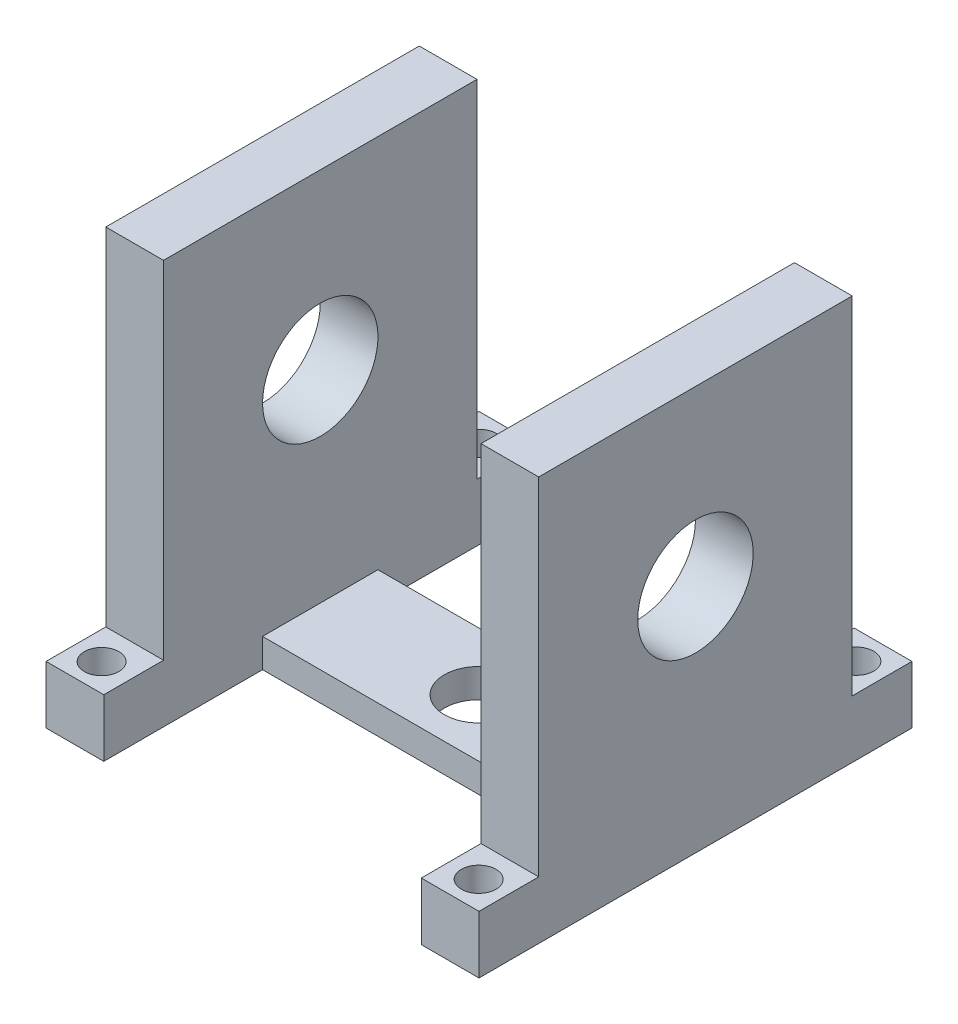
SolidWorks part; units mm, degrees
ref_plane "Front Plane" through (0, 0, 0) normal (0, 0, 1) x (1, 0, 0)
ref_plane "Top Plane" through (0, 0, 0) normal (0, 1, 0) x (1, 0, 0)
ref_plane "Right Plane" through (0, 0, 0) normal (1, 0, 0) x (0, 0, -1)
sketch "Sketch1" plane through (0, 0, 0) normal (0, 1, 0) x (1, 0, 0)
  line L0 (0, 0) -> (0, 37.5) construction
  line L1 (37.5, 37.5) -> (-37.5, 37.5)
  line L2 (37.5, 37.5) -> (37.5, -37.5)
  line L3 (37.5, -37.5) -> (-37.5, -37.5)
  line L4 (-37.5, 37.5) -> (-37.5, -37.5)
  line L5 (0, 0) -> (-37.5, 0) construction
  circle A0 centre (-32.66, 32.72) radius 3
  circle A1 centre (32.66, 32.72) radius 3
  circle A2 centre (32.66, -32.72) radius 3
  circle A3 centre (-32.66, -32.72) radius 3
  circle A4 centre (0, 0) radius 6
  point P0 (0, 0)
  point P11 (0, -37.5)
  dimension "D3" = 6
  dimension "D5" = 12
  dimension "D1" = 4.84
  dimension "D2" = 75
  dimension "D4" = 75
  dimension "D6" = 65.44
extrude "Boss-Extrude1" add sketch "Sketch1" along normal blind 10
sketch "Sketch2" plane through (0, 10, 0) normal (0, 1, 0) x (1, 0, 0)
  line L0 (-37.5, 37.5) -> (-37.5, -37.5) construction
  line L1 (-37.5, 27.1541) -> (-27.5, 27.1541)
  line L2 (-37.5, 27.1541) -> (-37.5, -27.1541)
  line L3 (0, 0) -> (0, 27.1541) construction
  line L4 (-27.5, 27.1541) -> (-27.5, -27.1541)
  line L5 (0, 0) -> (-23.3341, 0) construction
  line L6 (-37.5, -27.1541) -> (-27.5, -27.1541)
  line L7 (37.5, -27.1541) -> (27.5, -27.1541)
  line L8 (27.5, 27.1541) -> (27.5, -27.1541)
  line L9 (37.5, 27.1541) -> (37.5, -27.1541)
  line L10 (37.5, 27.1541) -> (27.5, 27.1541)
  point P12 (-27.5, 0)
  point P13 (-37.5, 0)
  point P17 (37.5, 0)
  point P18 (27.5, 0)
  dimension "D1" = 10
extrude "Boss-Extrude2" add sketch "Sketch2" along normal blind 60
sketch "Sketch3" plane through (-37.5, 0, 0) normal (-1, 0, 0) x (0, 0, 1)
  line L0 (0, 70) -> (0, 0) construction
  line L1 (-27.1541, 70) -> (27.1541, 70) construction
  line L2 (-27.1541, 40) -> (27.1541, 40) construction
  line L3 (-27.1541, 70) -> (-27.1541, 10) construction
  line L4 (27.1541, 70) -> (27.1541, 10) construction
  circle A0 centre (0, 40) radius 10
  dimension "D1" = 20
extrude "Cut-Extrude1" cut sketch "Sketch3" against normal through all both and the other way through all
sketch "Sketch4" plane through (0, 10, 0) normal (0, 1, 0) x (1, 0, 0)
  line L0 (0, 37.5) -> (0, -19.9966) construction
  line L1 (37.5, 37.5) -> (-37.5, 37.5) construction
  line L2 (-27.5, -27.1541) -> (-27.5, 27.1541) construction
  line L3 (27.5, -10) -> (-27.5, -10)
  line L4 (27.5, -10) -> (27.5, 10)
  line L5 (27.5, 10) -> (-27.5, 10)
  line L6 (-27.5, -10) -> (-27.5, 10)
  line L7 (27.5, -10) -> (-27.5, 10) construction
  line L8 (27.5, 10) -> (-27.5, -10) construction
  line L9 (-37.5, -37.5) -> (37.5, -37.5) construction
  line L10 (-27.5, 10) -> (27.5, 10)
  line L11 (-27.5, 10) -> (-27.5, 37.5)
  line L12 (-27.5, 37.5) -> (27.5, 37.5)
  line L13 (27.5, 10) -> (27.5, 37.5)
  line L14 (-27.5, -10) -> (27.5, -10)
  line L15 (-27.5, -10) -> (-27.5, -37.5)
  line L16 (-27.5, -37.5) -> (27.5, -37.5)
  line L17 (27.5, -10) -> (27.5, -37.5)
  point P5 (0, 0)
  point P13 (27.5, 0)
  line M13 (37.5, 37.5) -> (-37.5, 37.5)
  line M16 (-27.5, 27.1541) -> (-27.5, -27.1541)
  line M19 (-37.5, -37.5) -> (37.5, -37.5)
  line M22 (27.5, -27.1541) -> (27.5, 27.1541)
  dimension "D1" = 20
extrude "Cut-Extrude2" cut sketch "Sketch4" against normal through all both and the other way through all contours L13 L11 L5 M22 M13 M16 | L17 L3 L15 M22 M16 M19
sketch "Sketch5" plane through (0, 10, 0) normal (0, 1, 0) x (1, 0, 0)
  line L1 (27.5, 10) -> (-27.5, 10)
  line L2 (27.5, 10) -> (27.5, -10)
  line L3 (27.5, -10) -> (-27.5, -10)
  line L4 (-27.5, 10) -> (-27.5, -10)
  line L5 (27.5, 10) -> (-27.5, -10) construction
  line L6 (27.5, -10) -> (-27.5, 10) construction
  point P0 (0, 0)
extrude "Cut-Extrude3" cut sketch "Sketch5" against normal blind 5
